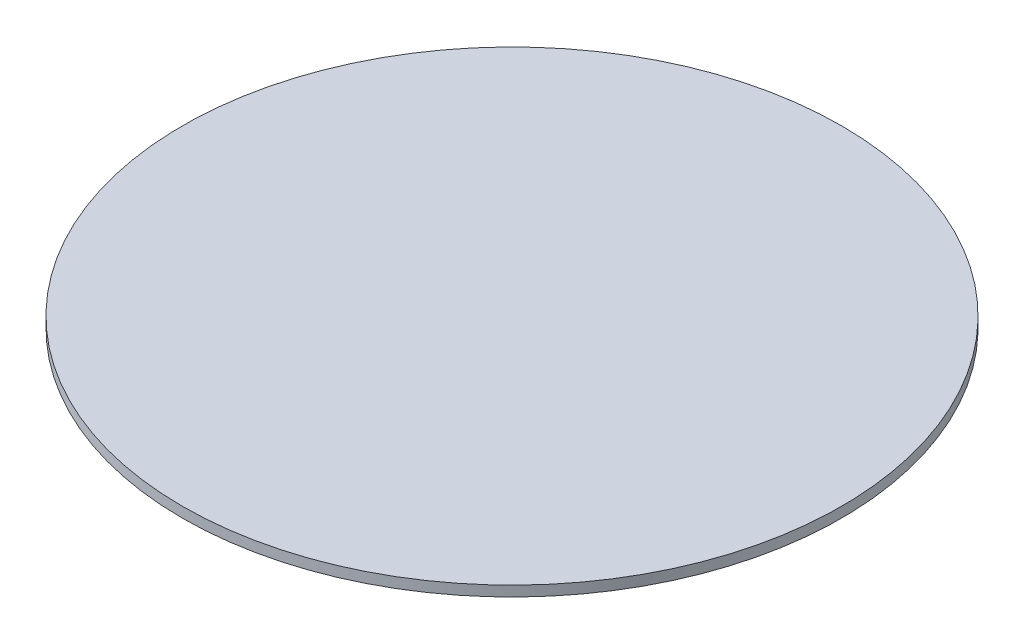
SolidWorks part; units mm, degrees
ref_plane "Front Plane" through (0, 0, 0) normal (0, 0, 1) x (1, 0, 0)
ref_plane "Top Plane" through (0, 0, 0) normal (0, 1, 0) x (1, 0, 0)
ref_plane "Right Plane" through (0, 0, 0) normal (1, 0, 0) x (0, 0, -1)
sketch "Sketch1" plane through (0, 0, 0) normal (0, 1, 0) x (1, 0, 0)
  circle A0 centre (0, 0) radius 50.8
  dimension "D1" = 101.6
extrude "Boss-Extrude1" add sketch "Sketch1" along normal blind 1.59
